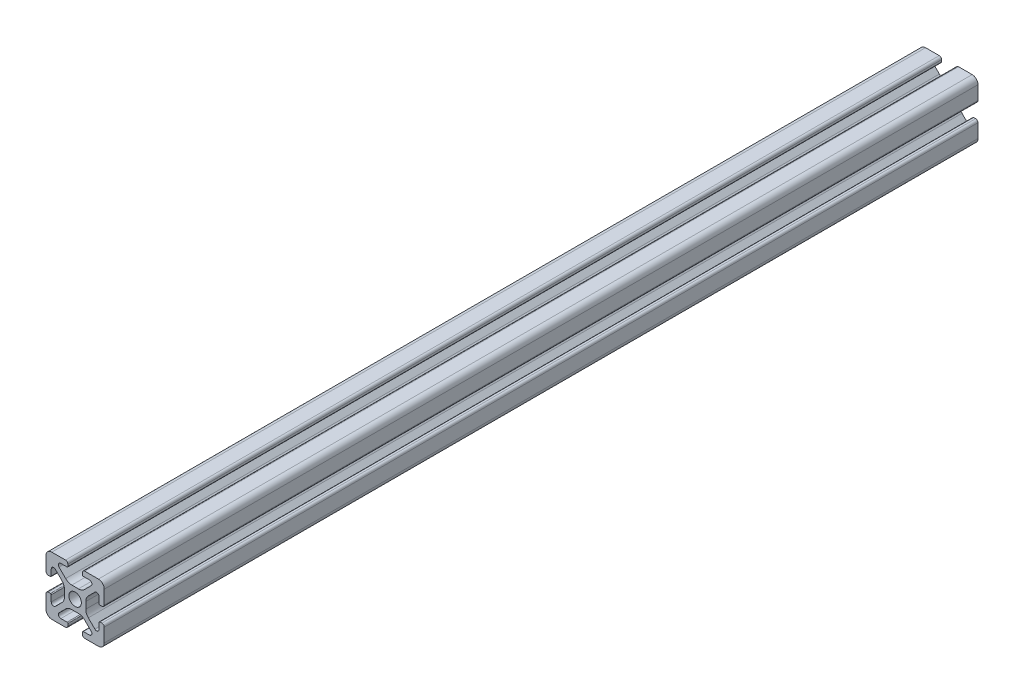
SolidWorks part; units mm, degrees
material "Alliage 1060"
ref_plane "Plan de face" through (0, 0, 0) normal (0, 0, 1) x (1, 0, 0)
ref_plane "Plan de dessus" through (0, 0, 0) normal (0, 1, 0) x (1, 0, 0)
ref_plane "Plan de droite" through (0, 0, 0) normal (1, 0, 0) x (0, 0, -1)
sketch "Esquisse1" plane through (0, 0, 0) normal (0, 0, 1) x (1, 0, 0)
  line L108 (-3.2559, 4.5287) -> (-5.5062, 6.779)
  line L109 (-4.9176, 8.2) -> (-2.8, 8.2)
  line L110 (-2.5, 8.5) -> (-2.5, 9.2)
  line L111 (-3.3, 10) -> (-8, 10)
  line L112 (-10, 8) -> (-10, 3.3)
  line L113 (-9.2, 2.5) -> (-8.5, 2.5)
  line L114 (-8.2, 2.8) -> (-8.2, 4.9176)
  line L115 (-6.779, 5.5062) -> (-4.5287, 3.2559)
  line L116 (-3.65, 1.1346) -> (-3.65, -1.1346)
  line L117 (-4.5287, -3.2559) -> (-6.779, -5.5062)
  line L118 (-8.2, -4.9176) -> (-8.2, -2.8)
  line L119 (-8.5, -2.5) -> (-9.2, -2.5)
  line L120 (-10, -3.3) -> (-10, -8)
  line L121 (-8, -10) -> (-3.3, -10)
  line L122 (-2.5, -9.2) -> (-2.5, -8.5)
  line L123 (-2.8, -8.2) -> (-4.9176, -8.2)
  line L124 (-5.5062, -6.779) -> (-3.2559, -4.5287)
  line L125 (-1.1346, -3.65) -> (1.1346, -3.65)
  line L126 (3.2559, -4.5287) -> (5.5062, -6.779)
  line L127 (4.9176, -8.2) -> (2.8, -8.2)
  line L128 (2.5, -8.5) -> (2.5, -9.2)
  line L129 (3.3, -10) -> (8, -10)
  line L130 (10, -8) -> (10, -3.3)
  line L131 (9.2, -2.5) -> (8.5, -2.5)
  line L132 (8.2, -2.8) -> (8.2, -4.9176)
  line L133 (6.779, -5.5062) -> (4.5287, -3.2559)
  line L134 (3.65, -1.1346) -> (3.65, 1.1346)
  line L135 (4.5287, 3.2559) -> (6.779, 5.5062)
  line L136 (8.2, 4.9176) -> (8.2, 2.8)
  line L137 (8.5, 2.5) -> (9.2, 2.5)
  line L138 (10, 3.3) -> (10, 8)
  line L139 (8, 10) -> (3.3, 10)
  line L140 (2.5, 9.2) -> (2.5, 8.5)
  line L141 (2.8, 8.2) -> (4.9176, 8.2)
  line L142 (5.5062, 6.779) -> (3.2559, 4.5287)
  line L143 (1.1346, 3.65) -> (-1.1346, 3.65)
  arc A42 (-2.15, 0) -> (2.15, 0) centre (0, 0) ccw
  arc A43 (2.15, 0) -> (-2.15, 0) centre (0, 0) ccw
  arc A108 (-4.9176, 8.2) -> (-5.5062, 6.779) centre (-4.9176, 7.3676) ccw
  arc A109 (-2.8, 8.2) -> (-2.5, 8.5) centre (-2.8, 8.5) ccw
  arc A110 (-2.5, 9.2) -> (-3.3, 10) centre (-3.3, 9.2) ccw
  arc A111 (-8, 10) -> (-10, 8) centre (-8, 8) ccw
  arc A112 (-10, 3.3) -> (-9.2, 2.5) centre (-9.2, 3.3) ccw
  arc A113 (-8.5, 2.5) -> (-8.2, 2.8) centre (-8.5, 2.8) ccw
  arc A114 (-6.779, 5.5062) -> (-8.2, 4.9176) centre (-7.3676, 4.9176) ccw
  arc A115 (-3.65, 1.1346) -> (-4.5287, 3.2559) centre (-6.65, 1.1346) ccw
  arc A116 (-4.5287, -3.2559) -> (-3.65, -1.1346) centre (-6.65, -1.1346) ccw
  arc A117 (-8.2, -4.9176) -> (-6.779, -5.5062) centre (-7.3676, -4.9176) ccw
  arc A118 (-8.2, -2.8) -> (-8.5, -2.5) centre (-8.5, -2.8) ccw
  arc A119 (-9.2, -2.5) -> (-10, -3.3) centre (-9.2, -3.3) ccw
  arc A120 (-10, -8) -> (-8, -10) centre (-8, -8) ccw
  arc A121 (-3.3, -10) -> (-2.5, -9.2) centre (-3.3, -9.2) ccw
  arc A122 (-2.5, -8.5) -> (-2.8, -8.2) centre (-2.8, -8.5) ccw
  arc A123 (-5.5062, -6.779) -> (-4.9176, -8.2) centre (-4.9176, -7.3676) ccw
  arc A124 (-1.1346, -3.65) -> (-3.2559, -4.5287) centre (-1.1346, -6.65) ccw
  arc A125 (3.2559, -4.5287) -> (1.1346, -3.65) centre (1.1346, -6.65) ccw
  arc A126 (4.9176, -8.2) -> (5.5062, -6.779) centre (4.9176, -7.3676) ccw
  arc A127 (2.8, -8.2) -> (2.5, -8.5) centre (2.8, -8.5) ccw
  arc A128 (2.5, -9.2) -> (3.3, -10) centre (3.3, -9.2) ccw
  arc A129 (8, -10) -> (10, -8) centre (8, -8) ccw
  arc A130 (10, -3.3) -> (9.2, -2.5) centre (9.2, -3.3) ccw
  arc A131 (8.5, -2.5) -> (8.2, -2.8) centre (8.5, -2.8) ccw
  arc A132 (6.779, -5.5062) -> (8.2, -4.9176) centre (7.3676, -4.9176) ccw
  arc A133 (3.65, -1.1346) -> (4.5287, -3.2559) centre (6.65, -1.1346) ccw
  arc A134 (4.5287, 3.2559) -> (3.65, 1.1346) centre (6.65, 1.1346) ccw
  arc A135 (8.2, 4.9176) -> (6.779, 5.5062) centre (7.3676, 4.9176) ccw
  arc A136 (8.2, 2.8) -> (8.5, 2.5) centre (8.5, 2.8) ccw
  arc A137 (9.2, 2.5) -> (10, 3.3) centre (9.2, 3.3) ccw
  arc A138 (10, 8) -> (8, 10) centre (8, 8) ccw
  arc A139 (3.3, 10) -> (2.5, 9.2) centre (3.3, 9.2) ccw
  arc A140 (2.5, 8.5) -> (2.8, 8.2) centre (2.8, 8.5) ccw
  arc A141 (5.5062, 6.779) -> (4.9176, 8.2) centre (4.9176, 7.3676) ccw
  arc A142 (1.1346, 3.65) -> (3.2559, 4.5287) centre (1.1346, 6.65) ccw
  arc A143 (-3.2559, 4.5287) -> (-1.1346, 3.65) centre (-1.1346, 6.65) ccw
extrude "Boss.-Extru.1" add sketch "Esquisse1" along normal blind 300
